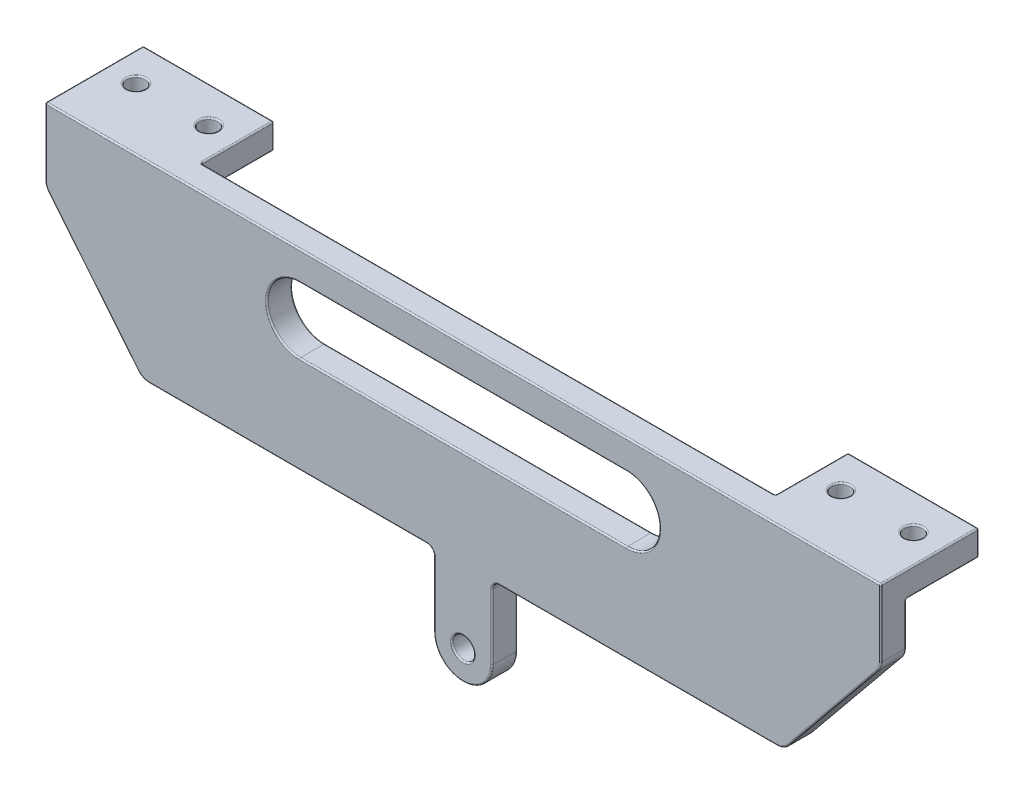
SolidWorks part; units mm, degrees
ref_plane "Front Plane" through (0, 0, 0) normal (0, 0, 1) x (1, 0, 0)
ref_plane "Top Plane" through (0, 0, 0) normal (0, 1, 0) x (1, 0, 0)
ref_plane "Right Plane" through (0, 0, 0) normal (1, 0, 0) x (0, 0, -1)
sketch "Sketch1" plane through (0, 0, 0) normal (0, 0, 1) x (1, 0, 0)
  line L0 (-100, 0) -> (100, 0) construction
  line L1 (-100, 0) -> (0, 100) construction
  line L2 (0, 100) -> (100, 0) construction
  line L3 (0, 0) -> (-50, 50) construction
  line L4 (-50, 50) -> (0, 0) construction
  line L5 (-40, 60) -> (40, 60) construction
  line L6 (0, 100) -> (0, 60) construction
  circle A0 centre (-100, 0) radius 20
  circle A1 centre (0, 0) radius 20
  circle A2 centre (100, 0) radius 20
  point P5 (0, 0)
  dimension "D5" = 40
  dimension "D1" = 200
  dimension "D2" = 90
  dimension "D3" = 90
  dimension "D4" = 80
sketch "Sketch2" plane through (0, 0, 0) normal (0, 0, 1) x (1, 0, 0)
  line L0 (-56.5165, 43.4835) -> (-40, 60) construction
  line L1 (-100, 0) -> (0, 100) construction
  line L2 (-40, 60) -> (40, 60) construction
  line L3 (40, 60) -> (86.565, 13.435) construction
  line L4 (0, 100) -> (100, 0) construction
  line L5 (-49.4454, 36.4124) -> (-35.8579, 50)
  line L6 (-35.8579, 50) -> (35.8579, 50)
  line L7 (35.8579, 50) -> (79.4939, 6.364)
  line L8 (-63.5876, 50.5546) -> (-44.1421, 70)
  line L9 (-44.1421, 70) -> (44.1421, 70)
  line L10 (44.1421, 70) -> (93.636, 20.5061)
  line L11 (-63.5876, 50.5546) -> (-49.4454, 36.4124)
  line L12 (93.636, 20.5061) -> (79.4939, 6.364)
  line L13 (81.9688, 8.8388) -> (95.4038, -4.5962)
  line L14 (91.1612, 18.0312) -> (104.5962, 4.5962)
  line L15 (75.9584, 9.8995) -> (90.1005, 24.0416) construction
  line L16 (0, 100) -> (0, 60) construction
  line L17 (-6, 70) -> (-3.4326, 85.5452)
  line L18 (6, 70) -> (3.4532, 85.4203)
  circle A0 centre (100, 0) radius 3.5
  circle A1 centre (100, 0) radius 10 construction
  arc A2 (95.4038, -4.5962) -> (104.5962, 4.5962) centre (100, 0) ccw
  circle A3 centre (100, 0) radius 0.5
  circle A4 centre (100, 0) radius 6.5 construction
  circle A5 centre (79.4939, 13.435) radius 1.8428
  circle A6 centre (86.565, 20.5061) radius 1.8428
  circle A7 centre (0, 60) radius 1.5
  circle A8 centre (0, 84.85) radius 1.5
  arc A9 (3.4532, 85.4203) -> (-3.4532, 85.4203) centre (0, 84.85) ccw
  circle A10 centre (0, 84.85) radius 3.5 construction
  circle A11 centre (-50, 50) radius 1.5
  dimension "D4" = 20
  dimension "D5" = 7
  dimension "D11" = 3
  dimension "D15" = 3
  dimension "D3" = 27.5
  dimension "D8" = 19
  dimension "D9" = 5
  dimension "D10" = 5
  dimension "5" = 5
  dimension "D12" = 14.85
  dimension "D7" = 6
  dimension "D14" = 6
  dimension "D1" = 10
  dimension "D2" = 10
  dimension "D6" = 3
  dimension "D13" = 2
sketch "Sketch3" plane through (0, 0, 0) normal (0, 0, 1) x (1, 0, 0)
  line L0 (-100, 0) -> (100, 0) construction
  line L1 (-86.6719, 13.3281) -> (-50, 50) construction
  line L2 (-24.0416, 9.8995) -> (-9.8995, 24.0416) construction
  line L3 (-50, 50) -> (-13.435, 13.435) construction
  line L4 (0, 0) -> (-50, 50) construction
  line L5 (-79.4939, 6.364) -> (-50, 35.8579)
  line L6 (-50, 35.8579) -> (-20.5061, 6.364)
  line L7 (-93.636, 20.5061) -> (-50, 64.1421)
  line L8 (-50, 64.1421) -> (-6.364, 20.5061)
  line L9 (-81.6799, 4.1779) -> (-50, 35.8579) construction
  line L10 (-95.8221, 18.3201) -> (-50, 64.1421) construction
  line L11 (-93.636, 20.5061) -> (-79.4939, 6.364)
  line L12 (-20.5061, 6.364) -> (-6.364, 20.5061)
  line L13 (-81.9688, 8.8388) -> (-95.4038, -4.5962)
  line L14 (-91.1612, 18.0312) -> (-104.5962, 4.5962)
  line L15 (-18.0312, 8.8388) -> (-4.5962, -4.5962)
  line L16 (-8.8388, 18.0312) -> (4.5962, 4.5962)
  line L17 (-88.751, 11.249) -> (-50, 50) construction
  line L18 (-90.1005, 24.0416) -> (-76.1469, 10.088) construction
  circle A0 centre (-100, 0) radius 10 construction
  circle A1 centre (-100, 0) radius 3.5
  circle A2 centre (0, 0) radius 10 construction
  circle A3 centre (0, 0) radius 3.5
  arc A4 (-4.5962, -4.5962) -> (4.5962, 4.5962) centre (0, 0) ccw
  arc A5 (-104.5962, 4.5962) -> (-95.4038, -4.5962) centre (-100, 0) ccw
  circle A6 centre (-86.565, 20.5061) radius 1
  circle A7 centre (0, 0) radius 6.5 construction
  circle A8 centre (-100, 0) radius 6.5 construction
  circle A9 centre (-79.4939, 13.435) radius 1
  circle A10 centre (-20.5061, 13.435) radius 1
  circle A11 centre (-13.435, 20.5061) radius 1
  circle A12 centre (-50, 50) radius 1.5 construction
  circle A13 centre (-50, 50) radius 1.5
  dimension "D1" = 20
  dimension "D2" = 7
  dimension "D9" = 2
  dimension "D7" = 19
  dimension "D8" = 19
  dimension "D10" = 5
  dimension "D11" = 5
  dimension "D12" = 5
  dimension "D13" = 5
  dimension "D14" = 5
  dimension "D15" = 5
  dimension "D3" = 3
  dimension "D4" = 3
  dimension "D5" = 10
  dimension "D6" = 10
sketch "Sketch4" plane through (0, 0, 0) normal (0, 0, 1) x (1, 0, 0)
  line L1 (57.5, 96.35) -> (57.5, 86.35)
  line L2 (57.5, 86.35) -> (44.1421, 70)
  line L3 (44.1421, 70) -> (4, 70)
  line L4 (-44.1421, 70) -> (-57.5, 86.35)
  line L5 (-57.5, 86.35) -> (-57.5, 96.35)
  line L7 (-57.5, 96.35) -> (57.5, 96.35)
  line L8 (-4, 60) -> (-4, 70)
  line L9 (4, 60) -> (4, 70)
  line L10 (-22.4799, 87.85) -> (22.5201, 87.85) construction
  line L11 (-22.4799, 92.35) -> (22.5201, 92.35)
  line L12 (-22.4799, 83.35) -> (22.5201, 83.35)
  line L13 (-4, 70) -> (-44.1421, 70)
  circle A0 centre (0, 60) radius 1.5 construction
  circle A1 centre (0, 60) radius 1.5
  arc A2 (-4, 60) -> (4, 60) centre (0, 60) ccw
  circle A3 centre (0, 60) radius 4 construction
  arc A4 (-22.4799, 92.35) -> (-22.4799, 83.35) centre (-22.4799, 87.85) ccw
  arc A5 (22.5201, 83.35) -> (22.5201, 92.35) centre (22.5201, 87.85) ccw
  circle A6 centre (0, 84.85) radius 1.5 construction
  point P0 (0, 96.35)
  point P22 (0.0201, 87.85)
  dimension "D1" = 115
  dimension "D2" = 10
  dimension "D4" = 45
  dimension "D5" = 9
  dimension "D6" = 45
  dimension "D7" = 4
  dimension "D3" = 2.5
extrude "Boss-Extrude1" add sketch "Sketch4" along normal blind 3.5
sketch "Sketch5" plane through (0, 96.35, 0) normal (0, 1, 0) x (1, 0, 0)
  line L0 (-57.5, 0) -> (-39.5, 0)
  line L1 (57.5, 0) -> (-57.5, 0) construction
  line L2 (-39.5, 0) -> (-39.5, 10)
  line L3 (-39.5, 10) -> (-57.5, 10)
  line L4 (-57.5, 10) -> (-57.5, 0)
  line L5 (-57.5, 5) -> (-39.5, 5) construction
  line L6 (-48.5, 5) -> (-48.5, 10) construction
  line L7 (0, 0) -> (0, 25.8798) construction
  line L8 (48.5, 5) -> (48.5, 10) construction
  line L9 (57.5, 5) -> (39.5, 5) construction
  line L10 (57.5, 10) -> (57.5, 0)
  line L11 (39.5, 10) -> (57.5, 10)
  line L12 (39.5, 0) -> (39.5, 10)
  line L13 (57.5, 0) -> (39.5, 0)
  circle A0 centre (-53.5, 5) radius 1.25
  circle A1 centre (-43.5, 5) radius 1.25
  circle A2 centre (43.5, 5) radius 1.25
  circle A3 centre (53.5, 5) radius 1.25
  dimension "D4" = 2.5
  dimension "D1" = 18
  dimension "D2" = 10
  dimension "D3" = 10
  dimension "D5" = 5
  dimension "D6" = 5
  dimension "D7" = 5
extrude "Boss-Extrude2" add sketch "Sketch5" against normal blind 3.5
fillet "Fillet1" radius 2 4 edges at (-44.1421, 70, 1.75) (-57.5, 86.35, 1.75) (44.1421, 70, 1.75) (57.5, 86.35, 1.75)
fillet "Fillet2" radius 1 2 edges at (4, 70, 1.75) (-4, 70, 1.75)
fillet "Fillet3" radius 0.2 70 edges at (57.5, 94.6, -10) (39.5, 94.6, 0) (39.5, 94.6, -10) (57.5, 92.85, -5) (48.5, 92.85, 0) (39.5, 92.85, -5) (48.5, 92.85, -10) (39.5, 96.35, -5) (48.5, 96.35, -10) (43.5, 92.85, -6.25) (43.5, 96.35, -6.25) (53.5, 92.85, -6.25) (53.5, 96.35, -6.25) (-43.5, 96.35, -3.75) (-43.5, 92.85, -3.75) (-53.5, 96.35, -3.75) (-53.5, 92.85, -3.75) (-39.5, 96.35, -5) (-48.5, 96.35, -10) (-57.5, 92.85, -5) (-48.5, 92.85, 0) (-39.5, 92.85, -5) (-48.5, 92.85, -10) (-39.5, 94.6, 0) (-39.5, 94.6, -10) (-57.5, 94.6, -10) (-26.9799, 87.85, 0) (0.0201, 83.35, 0) (27.0201, 87.85, 0) (0.0201, 92.35, 0) (-26.9799, 87.85, 3.5) (0.0201, 83.35, 3.5) (0.0201, 92.35, 3.5) (1.5, 60, 0) (1.5, 60, 3.5) (0, 96.35, 0) (-57.5, 89.9566, 0) (-50.8956, 78.2662, 0) (-24.0968, 70, 0) (-4, 64.5, 0) (0, 56, 0) (4, 64.5, 0) (24.0968, 70, 0) (50.8956, 78.2662, 0) (57.5, 89.9566, 0) (0, 96.35, 3.5) (-57.5, 91.7066, 3.5) (-50.8956, 78.2662, 3.5) (-24.0968, 70, 3.5) (-4, 64.5, 3.5) (0, 56, 3.5) (4, 64.5, 3.5) (24.0968, 70, 3.5) (50.8956, 78.2662, 3.5) (57.5, 91.7066, 3.5) (57.5, 96.35, -3.25) (-57.5, 96.35, -3.25) (57.3838, 86.3914, 0) (44.0506, 70.193, 0) (-57.3838, 86.3914, 0) (-44.0506, 70.193, 0) (57.3838, 86.3914, 3.5) (44.0506, 70.193, 3.5) (-57.3838, 86.3914, 3.5) (-44.0506, 70.193, 3.5) (4.2929, 69.7071, 0) (4.2929, 69.7071, 3.5) (-4.2929, 69.7071, 0) (-4.2929, 69.7071, 3.5) (27.0201, 87.85, 3.5)
